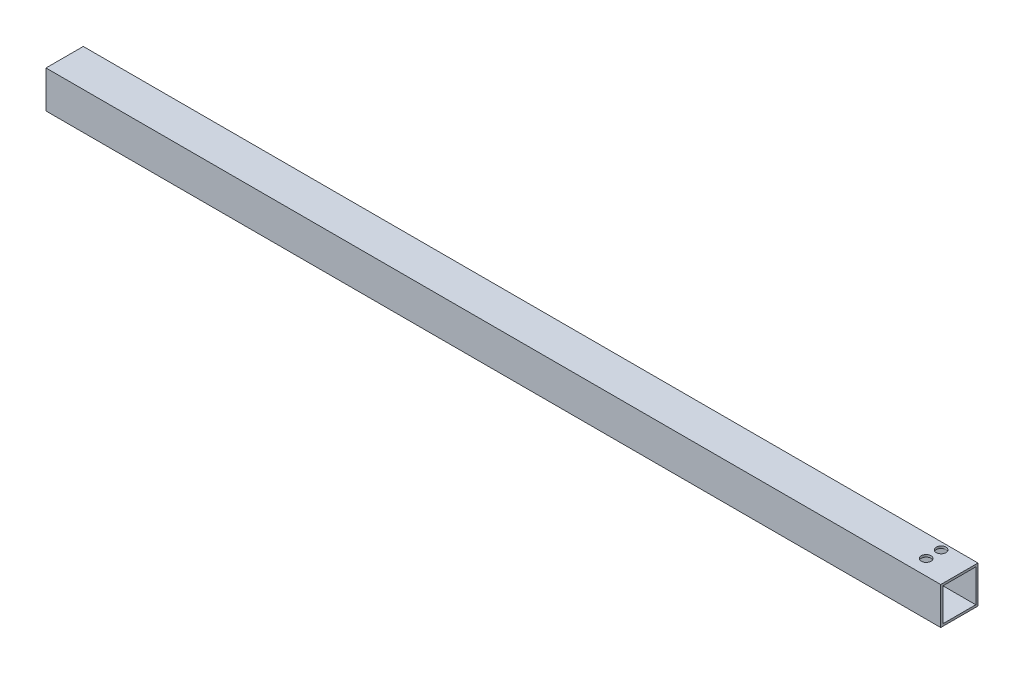
SolidWorks part; units mm, degrees
material "Cast Alloy Steel"
ref_plane "Front Plane" through (0, 0, 0) normal (0, 0, 1) x (1, 0, 0)
ref_plane "Top Plane" through (0, 0, 0) normal (0, 1, 0) x (1, 0, 0)
ref_plane "Right Plane" through (0, 0, 0) normal (1, 0, 0) x (0, 0, -1)
sketch "Sketch1" plane through (0, 0, 0) normal (1, 0, 0) x (0, 0, -1)
  line L0 (-22, 22) -> (-22, -22)
  line L1 (-22, 22) -> (22, 22)
  line L2 (-22, -22) -> (22, -22)
  line L3 (22, 22) -> (22, -22)
  line L4 (-22, 22) -> (22, -22) construction
  line L5 (-22, -22) -> (22, 22) construction
  line L6 (-25, 25) -> (25, 25)
  line L7 (25, 25) -> (25, -25)
  line L8 (-25, -25) -> (25, -25)
  line L9 (-25, 25) -> (-25, -25)
  point P1 (0, 0)
  dimension "D2" = 50
  dimension "D1" = 3
extrude "Boss-Extrude1" add sketch "Sketch1" along normal blind 1200
sketch "Sketch2" plane through (0, 0, -25) normal (0, 0, -1) x (-1, 0, 0)
  line L0 (-950, 25) -> (-950, -25) construction
  line L1 (-1200, 25) -> (0, 25) construction
  line L2 (-1200, -25) -> (0, -25) construction
  line L3 (-1200, -25) -> (-1200, 25) construction
  circle A0 centre (-950, 0) radius 19
  dimension "D1" = 38
  dimension "D2" = 250
extrude "Cut-Extrude1" cut sketch "Sketch2" against normal up to next
sketch "Sketch3" plane through (0, 25, 0) normal (0, 1, 0) x (1, 0, 0)
  line L0 (1160, -25) -> (1160, -4.5) construction
  line L1 (1200, -25) -> (0, -25) construction
  line L2 (1160, -4.5) -> (1160, 15.5) construction
  line L3 (1160, 15.5) -> (1160, 25) construction
  line L4 (1200, 25) -> (0, 25) construction
  line L5 (1200, 25) -> (1200, -25) construction
  line L6 (1200, 22) -> (0, 22) construction
  circle A0 centre (1160, -4.5) radius 6.5
  circle A1 centre (1160, 15.5) radius 6.5
  dimension "D1" = 13
  dimension "D2" = 20
  dimension "D3" = 40
extrude "Cut-Extrude2" cut sketch "Sketch3" against normal up to next
pattern_circular "CirPattern1" count 2 over 360 about axis through (950, 0, 25.001) along (0, 0, -1) of "Cut-Extrude2"
